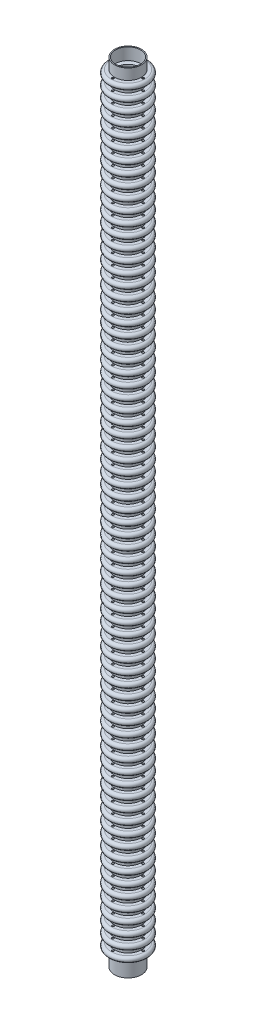
SolidWorks part; units mm, degrees
ref_plane "前视基准面" through (0, 0, 0) normal (0, 0, 1) x (1, 0, 0)
ref_plane "上视基准面" through (0, 0, 0) normal (0, 1, 0) x (1, 0, 0)
ref_plane "右视基准面" through (0, 0, 0) normal (1, 0, 0) x (0, 0, -1)
other "Configuration Table"
sketch "Sketch3" plane through (0, 0, 0) normal (0, 1, 0) x (1, 0, 0)
  circle A0 centre (0, 0) radius 125
  dimension "D1" = 250
extrude "Boss-Extrude1" add sketch "Sketch3" against normal blind 7300
sketch "Sketch9" plane through (0, 0, 0) normal (0, 0, 1) x (1, 0, 0)
  line L0 (125, -100) -> (155, -100)
  line L1 (125, -7300) -> (125, 0) construction
  line L2 (155, -150) -> (125, -150)
  line L3 (125, -150) -> (125, -100)
  arc A0 (155, -100) -> (155, -150) centre (155, -125) cw
  dimension "D1" = 30
  dimension "D2" = 50
  dimension "D3" = 100
revolve "Revolve1" add sketch "Sketch9" angle 360 about axis through (0, -7300, 0) along (0, 1, 0)
shell "Shell1" thickness 10
sketch "Sketch11" plane through (0, -100, 0) normal (0, 1, 0) x (1, 0, 0)
  circle A0 centre (0, 140) radius 10
  circle A1 centre (-140, 0) radius 10
  dimension "D3" = 20
  dimension "D1" = 140
  dimension "D2" = 140
extrude "Cut-Extrude1" cut sketch "Sketch11" against normal through all
pattern_linear "LPattern2" count 71 spacing 100 along (0, -1, 0) of "Revolve1"
mirror "Mirror2" about plane through (0, 0, 0) normal (1, 0, 0) of "Cut-Extrude1" second plane through (0, 0, 0) second plane normal (0, 0, 1)
